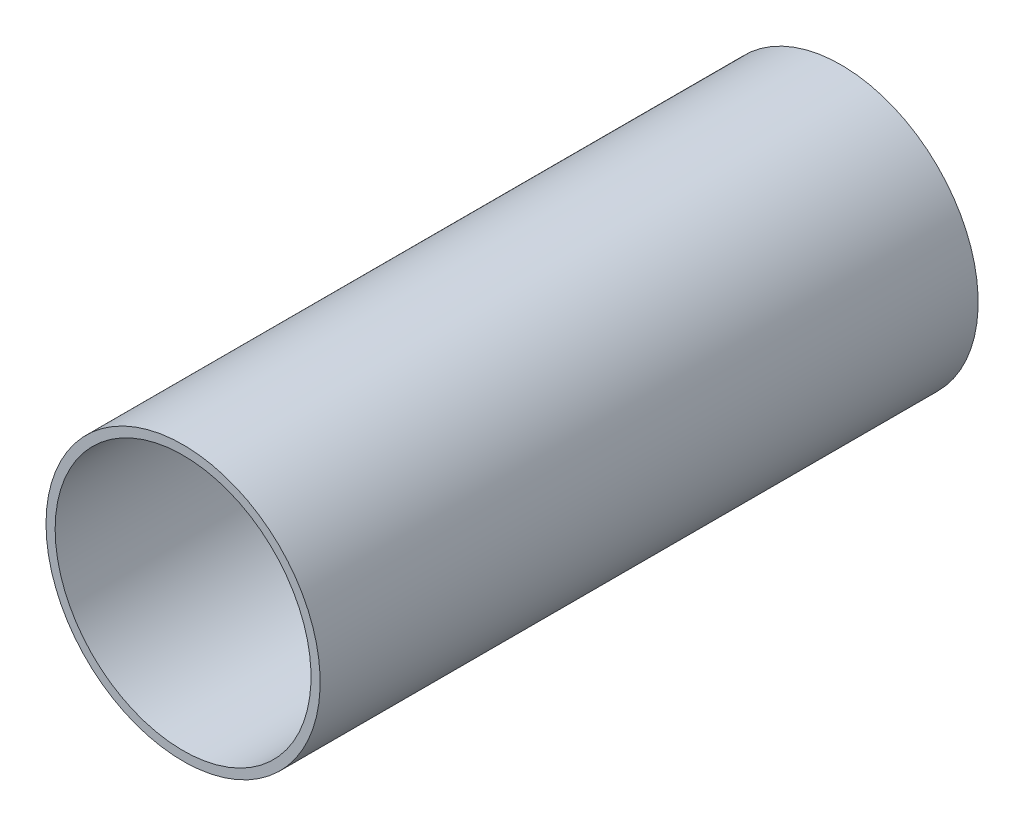
SolidWorks part; units mm, degrees
material "6063-T6"
ref_plane "Plano frontal" through (0, 0, 0) normal (0, 0, 1) x (1, 0, 0)
ref_plane "Plano superior" through (0, 0, 0) normal (0, 1, 0) x (1, 0, 0)
ref_plane "Plano direito" through (0, 0, 0) normal (1, 0, 0) x (0, 0, -1)
sketch "Esboço1" plane through (0, 0, 0) normal (0, 0, 1) x (1, 0, 0)
  circle A0 centre (0, 0) radius 70
  circle A1 centre (0, 0) radius 75
  dimension "D1" = 140
  dimension "D2" = 150
extrude "Ressalto-extrusão1" add sketch "Esboço1" along normal blind 360 contours A0
